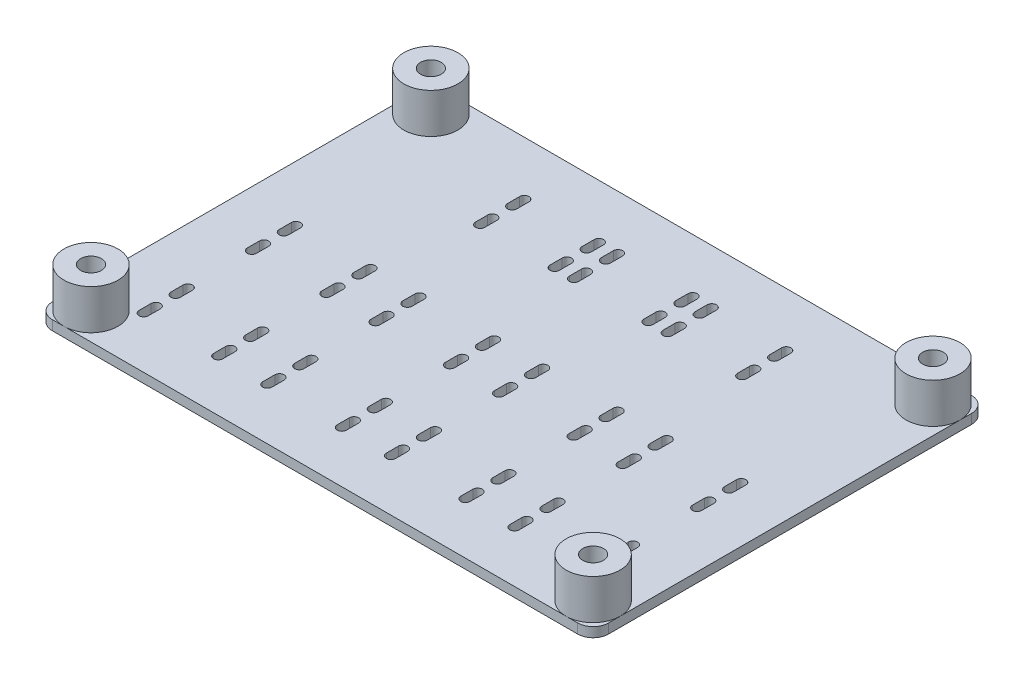
SolidWorks part; units mm, degrees
ref_plane "Front Plane" through (0, 0, 0) normal (0, 0, 1) x (1, 0, 0)
ref_plane "Top Plane" through (0, 0, 0) normal (0, 1, 0) x (1, 0, 0)
ref_plane "Right Plane" through (0, 0, 0) normal (1, 0, 0) x (0, 0, -1)
sketch "Sketch1" plane through (0, 0, 0) normal (0, 1, 0) x (1, 0, 0)
  line L0 (-36.605, 1.085) -> (-36.605, -0.915) construction
  line L1 (-41.275, -27.94) -> (41.275, -27.94) construction
  line L2 (-41.275, -27.94) -> (-41.275, 27.94) construction
  line L3 (-41.275, 27.94) -> (41.275, 27.94) construction
  line L4 (41.275, -27.94) -> (41.275, 27.94) construction
  line L5 (-41.275, -27.94) -> (41.275, 27.94) construction
  line L6 (-41.275, 27.94) -> (41.275, -27.94) construction
  line L7 (-45.72, -32.385) -> (45.72, -32.385)
  line L8 (-45.72, -32.385) -> (-45.72, 32.385)
  line L9 (-45.72, 32.385) -> (45.72, 32.385)
  line L10 (45.72, -32.385) -> (45.72, 32.385)
  line L11 (-45.72, -32.385) -> (45.72, 32.385) construction
  line L12 (-45.72, 32.385) -> (45.72, -32.385) construction
  line L13 (-30.48, -2.54) -> (30.48, -2.54) construction
  line L14 (-16.285, -5.165) -> (-4.035, -5.165) construction
  line L15 (-55, 0) -> (55, 0) construction
  line L16 (0, -55) -> (0, 55) construction
  line L17 (-15.1961, -11.43) -> (15.1961, -11.43) construction
  line L18 (-36.605, -5.165) -> (-24.355, -5.165) construction
  line L19 (-36.605, -5.165) -> (-36.605, 0.085) construction
  line L20 (-36.605, 0.085) -> (-24.355, 0.085) construction
  line L21 (-24.355, -5.165) -> (-24.355, 0.085) construction
  line L22 (-36.605, -5.165) -> (-24.355, 0.085) construction
  line L23 (-36.605, 0.085) -> (-24.355, -5.165) construction
  line L28 (-16.285, -5.165) -> (-16.285, 0.085) construction
  line L34 (-16.285, 0.085) -> (-4.035, 0.085) construction
  line L36 (-4.035, -5.165) -> (-4.035, 0.085) construction
  line L37 (-16.285, -5.165) -> (-4.035, 0.085) construction
  line L38 (-16.285, 0.085) -> (-4.035, -5.165) construction
  line L39 (4.035, -5.165) -> (16.285, -5.165) construction
  line L40 (4.035, -5.165) -> (4.035, 0.085) construction
  line L41 (4.035, 0.085) -> (16.285, 0.085) construction
  line L42 (16.285, -5.165) -> (16.285, 0.085) construction
  line L43 (4.035, -5.165) -> (16.285, 0.085) construction
  line L44 (4.035, 0.085) -> (16.285, -5.165) construction
  line L45 (24.355, -5.165) -> (36.605, -5.165) construction
  line L46 (24.355, -5.165) -> (24.355, 0.085) construction
  line L47 (24.355, 0.085) -> (36.605, 0.085) construction
  line L48 (36.605, -5.165) -> (36.605, 0.085) construction
  line L49 (24.355, -5.165) -> (36.605, 0.085) construction
  line L50 (24.355, 0.085) -> (36.605, -5.165) construction
  line L51 (-35.843, 1.085) -> (-35.843, -0.915)
  line L52 (-37.367, 1.085) -> (-37.367, -0.915)
  line L53 (-24.355, 1.085) -> (-24.355, -0.915) construction
  line L54 (-23.593, 1.085) -> (-23.593, -0.915)
  line L55 (-25.117, 1.085) -> (-25.117, -0.915)
  line L56 (-36.605, -4.165) -> (-36.605, -6.165) construction
  line L57 (-35.843, -4.165) -> (-35.843, -6.165)
  line L58 (-37.367, -4.165) -> (-37.367, -6.165)
  line L59 (-24.355, -4.165) -> (-24.355, -6.165) construction
  line L60 (-23.593, -4.165) -> (-23.593, -6.165)
  line L61 (-25.117, -4.165) -> (-25.117, -6.165)
  line L62 (-16.285, 1.085) -> (-16.285, -0.915) construction
  line L63 (-15.523, 1.085) -> (-15.523, -0.915)
  line L64 (-17.047, 1.085) -> (-17.047, -0.915)
  line L65 (-4.035, 1.085) -> (-4.035, -0.915) construction
  line L66 (-3.273, 1.085) -> (-3.273, -0.915)
  line L67 (-4.797, 1.085) -> (-4.797, -0.915)
  line L68 (-16.285, -4.165) -> (-16.285, -6.165) construction
  line L69 (-15.523, -4.165) -> (-15.523, -6.165)
  line L70 (-17.047, -4.165) -> (-17.047, -6.165)
  line L71 (-4.035, -4.165) -> (-4.035, -6.165) construction
  line L72 (-3.273, -4.165) -> (-3.273, -6.165)
  line L73 (-4.797, -4.165) -> (-4.797, -6.165)
  line L74 (4.035, 1.085) -> (4.035, -0.915) construction
  line L75 (4.797, 1.085) -> (4.797, -0.915)
  line L76 (3.273, 1.085) -> (3.273, -0.915)
  line L77 (16.285, 1.085) -> (16.285, -0.915) construction
  line L78 (17.047, 1.085) -> (17.047, -0.915)
  line L79 (15.523, 1.085) -> (15.523, -0.915)
  line L80 (4.035, -4.165) -> (4.035, -6.165) construction
  line L81 (4.797, -4.165) -> (4.797, -6.165)
  line L82 (3.273, -4.165) -> (3.273, -6.165)
  line L83 (16.285, -4.165) -> (16.285, -6.165) construction
  line L84 (17.047, -4.165) -> (17.047, -6.165)
  line L85 (15.523, -4.165) -> (15.523, -6.165)
  line L86 (24.355, 1.085) -> (24.355, -0.915) construction
  line L87 (25.117, 1.085) -> (25.117, -0.915)
  line L88 (23.593, 1.085) -> (23.593, -0.915)
  line L89 (24.355, -4.165) -> (24.355, -6.165) construction
  line L90 (25.117, -4.165) -> (25.117, -6.165)
  line L91 (23.593, -4.165) -> (23.593, -6.165)
  line L92 (36.605, -4.165) -> (36.605, -6.165) construction
  line L93 (37.367, -4.165) -> (37.367, -6.165)
  line L94 (35.843, -4.165) -> (35.843, -6.165)
  line L95 (24.355, -18.695) -> (24.355, -16.695) construction
  line L98 (36.605, 1.085) -> (36.605, -0.915) construction
  line L99 (37.367, 1.085) -> (37.367, -0.915)
  line L100 (35.843, 1.085) -> (35.843, -0.915)
  line L101 (25.117, -18.695) -> (25.117, -16.695)
  line L102 (23.593, -18.695) -> (23.593, -16.695)
  line L103 (24.355, -23.945) -> (24.355, -21.945) construction
  line L104 (25.117, -23.945) -> (25.117, -21.945)
  line L105 (23.593, -23.945) -> (23.593, -21.945)
  line L106 (16.285, -23.945) -> (16.285, -21.945) construction
  line L107 (17.047, -23.945) -> (17.047, -21.945)
  line L108 (15.523, -23.945) -> (15.523, -21.945)
  line L109 (16.285, -18.695) -> (16.285, -16.695) construction
  line L110 (17.047, -18.695) -> (17.047, -16.695)
  line L111 (15.523, -18.695) -> (15.523, -16.695)
  line L112 (4.035, -23.945) -> (4.035, -21.945) construction
  line L113 (4.797, -23.945) -> (4.797, -21.945)
  line L114 (3.273, -23.945) -> (3.273, -21.945)
  line L115 (4.035, -18.695) -> (4.035, -16.695) construction
  line L116 (4.797, -18.695) -> (4.797, -16.695)
  line L117 (3.273, -18.695) -> (3.273, -16.695)
  line L118 (-4.035, -18.695) -> (-4.035, -16.695) construction
  line L119 (-3.273, -18.695) -> (-3.273, -16.695)
  line L120 (-4.797, -18.695) -> (-4.797, -16.695)
  line L121 (-4.035, -23.945) -> (-4.035, -21.945) construction
  line L122 (-3.273, -23.945) -> (-3.273, -21.945)
  line L123 (-4.797, -23.945) -> (-4.797, -21.945)
  line L124 (-16.285, -23.945) -> (-16.285, -21.945) construction
  line L125 (-15.523, -23.945) -> (-15.523, -21.945)
  line L126 (-17.047, -23.945) -> (-17.047, -21.945)
  line L127 (-16.285, -18.695) -> (-16.285, -16.695) construction
  line L128 (-15.523, -18.695) -> (-15.523, -16.695)
  line L129 (-17.047, -18.695) -> (-17.047, -16.695)
  line L130 (-24.355, -23.945) -> (-24.355, -21.945) construction
  line L131 (-23.593, -23.945) -> (-23.593, -21.945)
  line L132 (-25.117, -23.945) -> (-25.117, -21.945)
  line L133 (-24.355, -18.695) -> (-24.355, -16.695) construction
  line L134 (-23.593, -18.695) -> (-23.593, -16.695)
  line L135 (-25.117, -18.695) -> (-25.117, -16.695)
  line L136 (-36.605, -18.695) -> (-36.605, -16.695) construction
  line L137 (-35.843, -18.695) -> (-35.843, -16.695)
  line L138 (-37.367, -18.695) -> (-37.367, -16.695)
  line L139 (-36.605, -23.945) -> (-36.605, -21.945) construction
  line L140 (-35.843, -23.945) -> (-35.843, -21.945)
  line L141 (-37.367, -23.945) -> (-37.367, -21.945)
  line L142 (36.605, -23.945) -> (36.605, -21.945) construction
  line L143 (37.367, -23.945) -> (37.367, -21.945)
  line L144 (35.843, -23.945) -> (35.843, -21.945)
  line L145 (36.605, -18.695) -> (36.605, -16.695) construction
  line L146 (37.367, -18.695) -> (37.367, -16.695)
  line L147 (35.843, -18.695) -> (35.843, -16.695)
  line L148 (0, -2.54) -> (0, 19.9314) construction
  line L149 (-15.41, 19.9314) -> (15.41, 19.9314) construction
  line L150 (-21.535, 21.5564) -> (-21.535, 23.5564) construction
  line L151 (-6.125, 17.3064) -> (6.125, 17.3064) construction
  line L152 (-6.125, 17.3064) -> (-6.125, 22.5564) construction
  line L153 (-6.125, 22.5564) -> (6.125, 22.5564) construction
  line L154 (6.125, 17.3064) -> (6.125, 22.5564) construction
  line L155 (-6.125, 17.3064) -> (6.125, 22.5564) construction
  line L156 (-6.125, 22.5564) -> (6.125, 17.3064) construction
  line L157 (-21.535, 17.3064) -> (-9.285, 17.3064) construction
  line L158 (-21.535, 17.3064) -> (-21.535, 22.5564) construction
  line L159 (-21.535, 22.5564) -> (-9.285, 22.5564) construction
  line L160 (-9.285, 17.3064) -> (-9.285, 22.5564) construction
  line L161 (-21.535, 17.3064) -> (-9.285, 22.5564) construction
  line L162 (-21.535, 22.5564) -> (-9.285, 17.3064) construction
  line L163 (9.285, 17.3064) -> (21.535, 17.3064) construction
  line L164 (9.285, 17.3064) -> (9.285, 22.5564) construction
  line L165 (9.285, 22.5564) -> (21.535, 22.5564) construction
  line L166 (21.535, 17.3064) -> (21.535, 22.5564) construction
  line L167 (9.285, 17.3064) -> (21.535, 22.5564) construction
  line L168 (9.285, 22.5564) -> (21.535, 17.3064) construction
  line L169 (-22.297, 21.5564) -> (-22.297, 23.5564)
  line L170 (-20.773, 21.5564) -> (-20.773, 23.5564)
  line L171 (9.285, 21.5564) -> (9.285, 23.5564) construction
  line L172 (8.523, 21.5564) -> (8.523, 23.5564)
  line L173 (10.047, 21.5564) -> (10.047, 23.5564)
  line L174 (6.125, 21.5564) -> (6.125, 23.5564) construction
  line L175 (5.363, 21.5564) -> (5.363, 23.5564)
  line L176 (6.887, 21.5564) -> (6.887, 23.5564)
  line L177 (-9.285, 21.5564) -> (-9.285, 23.5564) construction
  line L178 (-10.047, 21.5564) -> (-10.047, 23.5564)
  line L179 (-8.523, 21.5564) -> (-8.523, 23.5564)
  line L180 (-6.125, 21.5564) -> (-6.125, 23.5564) construction
  line L181 (-6.887, 21.5564) -> (-6.887, 23.5564)
  line L182 (-5.363, 21.5564) -> (-5.363, 23.5564)
  line L183 (21.535, 21.5564) -> (21.535, 23.5564) construction
  line L184 (20.773, 21.5564) -> (20.773, 23.5564)
  line L185 (22.297, 21.5564) -> (22.297, 23.5564)
  line L186 (21.535, 18.3064) -> (21.535, 16.3064) construction
  line L187 (20.773, 18.3064) -> (20.773, 16.3064)
  line L188 (22.297, 18.3064) -> (22.297, 16.3064)
  line L189 (9.285, 18.3064) -> (9.285, 16.3064) construction
  line L190 (8.523, 18.3064) -> (8.523, 16.3064)
  line L191 (10.047, 18.3064) -> (10.047, 16.3064)
  line L192 (6.125, 18.3064) -> (6.125, 16.3064) construction
  line L193 (5.363, 18.3064) -> (5.363, 16.3064)
  line L194 (6.887, 18.3064) -> (6.887, 16.3064)
  line L195 (-6.125, 18.3064) -> (-6.125, 16.3064) construction
  line L196 (-6.887, 18.3064) -> (-6.887, 16.3064)
  line L197 (-5.363, 18.3064) -> (-5.363, 16.3064)
  line L198 (-9.285, 18.3064) -> (-9.285, 16.3064) construction
  line L199 (-10.047, 18.3064) -> (-10.047, 16.3064)
  line L200 (-8.523, 18.3064) -> (-8.523, 16.3064)
  line L201 (-21.535, 18.3064) -> (-21.535, 16.3064) construction
  line L202 (-22.297, 18.3064) -> (-22.297, 16.3064)
  line L203 (-20.773, 18.3064) -> (-20.773, 16.3064)
  arc A4 (-35.843, 1.085) -> (-37.367, 1.085) centre (-36.605, 1.085) ccw
  arc A5 (-37.367, -0.915) -> (-35.843, -0.915) centre (-36.605, -0.915) ccw
  arc A6 (-23.593, 1.085) -> (-25.117, 1.085) centre (-24.355, 1.085) ccw
  arc A7 (-25.117, -0.915) -> (-23.593, -0.915) centre (-24.355, -0.915) ccw
  arc A8 (-35.843, -4.165) -> (-37.367, -4.165) centre (-36.605, -4.165) ccw
  arc A9 (-37.367, -6.165) -> (-35.843, -6.165) centre (-36.605, -6.165) ccw
  arc A10 (-23.593, -4.165) -> (-25.117, -4.165) centre (-24.355, -4.165) ccw
  arc A11 (-25.117, -6.165) -> (-23.593, -6.165) centre (-24.355, -6.165) ccw
  arc A12 (-15.523, 1.085) -> (-17.047, 1.085) centre (-16.285, 1.085) ccw
  arc A13 (-17.047, -0.915) -> (-15.523, -0.915) centre (-16.285, -0.915) ccw
  arc A14 (-3.273, 1.085) -> (-4.797, 1.085) centre (-4.035, 1.085) ccw
  arc A15 (-4.797, -0.915) -> (-3.273, -0.915) centre (-4.035, -0.915) ccw
  arc A16 (-15.523, -4.165) -> (-17.047, -4.165) centre (-16.285, -4.165) ccw
  arc A17 (-17.047, -6.165) -> (-15.523, -6.165) centre (-16.285, -6.165) ccw
  arc A18 (-3.273, -4.165) -> (-4.797, -4.165) centre (-4.035, -4.165) ccw
  arc A19 (-4.797, -6.165) -> (-3.273, -6.165) centre (-4.035, -6.165) ccw
  arc A20 (4.797, 1.085) -> (3.273, 1.085) centre (4.035, 1.085) ccw
  arc A21 (3.273, -0.915) -> (4.797, -0.915) centre (4.035, -0.915) ccw
  arc A22 (17.047, 1.085) -> (15.523, 1.085) centre (16.285, 1.085) ccw
  arc A23 (15.523, -0.915) -> (17.047, -0.915) centre (16.285, -0.915) ccw
  arc A24 (4.797, -4.165) -> (3.273, -4.165) centre (4.035, -4.165) ccw
  arc A25 (3.273, -6.165) -> (4.797, -6.165) centre (4.035, -6.165) ccw
  arc A26 (17.047, -4.165) -> (15.523, -4.165) centre (16.285, -4.165) ccw
  arc A27 (15.523, -6.165) -> (17.047, -6.165) centre (16.285, -6.165) ccw
  arc A28 (25.117, 1.085) -> (23.593, 1.085) centre (24.355, 1.085) ccw
  arc A29 (23.593, -0.915) -> (25.117, -0.915) centre (24.355, -0.915) ccw
  arc A30 (25.117, -4.165) -> (23.593, -4.165) centre (24.355, -4.165) ccw
  arc A31 (23.593, -6.165) -> (25.117, -6.165) centre (24.355, -6.165) ccw
  arc A32 (37.367, -4.165) -> (35.843, -4.165) centre (36.605, -4.165) ccw
  arc A33 (35.843, -6.165) -> (37.367, -6.165) centre (36.605, -6.165) ccw
  arc A36 (37.367, 1.085) -> (35.843, 1.085) centre (36.605, 1.085) ccw
  arc A37 (35.843, -0.915) -> (37.367, -0.915) centre (36.605, -0.915) ccw
  arc A38 (25.117, -18.695) -> (23.593, -18.695) centre (24.355, -18.695) cw
  arc A39 (23.593, -16.695) -> (25.117, -16.695) centre (24.355, -16.695) cw
  arc A40 (25.117, -23.945) -> (23.593, -23.945) centre (24.355, -23.945) cw
  arc A41 (23.593, -21.945) -> (25.117, -21.945) centre (24.355, -21.945) cw
  arc A42 (17.047, -23.945) -> (15.523, -23.945) centre (16.285, -23.945) cw
  arc A43 (15.523, -21.945) -> (17.047, -21.945) centre (16.285, -21.945) cw
  arc A44 (17.047, -18.695) -> (15.523, -18.695) centre (16.285, -18.695) cw
  arc A45 (15.523, -16.695) -> (17.047, -16.695) centre (16.285, -16.695) cw
  arc A46 (4.797, -23.945) -> (3.273, -23.945) centre (4.035, -23.945) cw
  arc A47 (3.273, -21.945) -> (4.797, -21.945) centre (4.035, -21.945) cw
  arc A48 (4.797, -18.695) -> (3.273, -18.695) centre (4.035, -18.695) cw
  arc A49 (3.273, -16.695) -> (4.797, -16.695) centre (4.035, -16.695) cw
  arc A50 (-3.273, -18.695) -> (-4.797, -18.695) centre (-4.035, -18.695) cw
  arc A51 (-4.797, -16.695) -> (-3.273, -16.695) centre (-4.035, -16.695) cw
  arc A52 (-3.273, -23.945) -> (-4.797, -23.945) centre (-4.035, -23.945) cw
  arc A53 (-4.797, -21.945) -> (-3.273, -21.945) centre (-4.035, -21.945) cw
  arc A54 (-15.523, -23.945) -> (-17.047, -23.945) centre (-16.285, -23.945) cw
  arc A55 (-17.047, -21.945) -> (-15.523, -21.945) centre (-16.285, -21.945) cw
  arc A56 (-15.523, -18.695) -> (-17.047, -18.695) centre (-16.285, -18.695) cw
  arc A57 (-17.047, -16.695) -> (-15.523, -16.695) centre (-16.285, -16.695) cw
  arc A58 (-23.593, -23.945) -> (-25.117, -23.945) centre (-24.355, -23.945) cw
  arc A59 (-25.117, -21.945) -> (-23.593, -21.945) centre (-24.355, -21.945) cw
  arc A60 (-23.593, -18.695) -> (-25.117, -18.695) centre (-24.355, -18.695) cw
  arc A61 (-25.117, -16.695) -> (-23.593, -16.695) centre (-24.355, -16.695) cw
  arc A62 (-35.843, -18.695) -> (-37.367, -18.695) centre (-36.605, -18.695) cw
  arc A63 (-37.367, -16.695) -> (-35.843, -16.695) centre (-36.605, -16.695) cw
  arc A64 (-35.843, -23.945) -> (-37.367, -23.945) centre (-36.605, -23.945) cw
  arc A65 (-37.367, -21.945) -> (-35.843, -21.945) centre (-36.605, -21.945) cw
  arc A66 (37.367, -23.945) -> (35.843, -23.945) centre (36.605, -23.945) cw
  arc A67 (35.843, -21.945) -> (37.367, -21.945) centre (36.605, -21.945) cw
  arc A68 (37.367, -18.695) -> (35.843, -18.695) centre (36.605, -18.695) cw
  arc A69 (35.843, -16.695) -> (37.367, -16.695) centre (36.605, -16.695) cw
  arc A70 (-22.297, 21.5564) -> (-20.773, 21.5564) centre (-21.535, 21.5564) ccw
  arc A71 (-20.773, 23.5564) -> (-22.297, 23.5564) centre (-21.535, 23.5564) ccw
  arc A72 (8.523, 21.5564) -> (10.047, 21.5564) centre (9.285, 21.5564) ccw
  arc A73 (10.047, 23.5564) -> (8.523, 23.5564) centre (9.285, 23.5564) ccw
  arc A74 (5.363, 21.5564) -> (6.887, 21.5564) centre (6.125, 21.5564) ccw
  arc A75 (6.887, 23.5564) -> (5.363, 23.5564) centre (6.125, 23.5564) ccw
  arc A76 (-10.047, 21.5564) -> (-8.523, 21.5564) centre (-9.285, 21.5564) ccw
  arc A77 (-8.523, 23.5564) -> (-10.047, 23.5564) centre (-9.285, 23.5564) ccw
  arc A78 (-6.887, 21.5564) -> (-5.363, 21.5564) centre (-6.125, 21.5564) ccw
  arc A79 (-5.363, 23.5564) -> (-6.887, 23.5564) centre (-6.125, 23.5564) ccw
  arc A80 (20.773, 21.5564) -> (22.297, 21.5564) centre (21.535, 21.5564) ccw
  arc A81 (22.297, 23.5564) -> (20.773, 23.5564) centre (21.535, 23.5564) ccw
  arc A82 (20.773, 18.3064) -> (22.297, 18.3064) centre (21.535, 18.3064) cw
  arc A83 (22.297, 16.3064) -> (20.773, 16.3064) centre (21.535, 16.3064) cw
  arc A84 (8.523, 18.3064) -> (10.047, 18.3064) centre (9.285, 18.3064) cw
  arc A85 (10.047, 16.3064) -> (8.523, 16.3064) centre (9.285, 16.3064) cw
  arc A86 (5.363, 18.3064) -> (6.887, 18.3064) centre (6.125, 18.3064) cw
  arc A87 (6.887, 16.3064) -> (5.363, 16.3064) centre (6.125, 16.3064) cw
  arc A88 (-6.887, 18.3064) -> (-5.363, 18.3064) centre (-6.125, 18.3064) cw
  arc A89 (-5.363, 16.3064) -> (-6.887, 16.3064) centre (-6.125, 16.3064) cw
  arc A90 (-10.047, 18.3064) -> (-8.523, 18.3064) centre (-9.285, 18.3064) cw
  arc A91 (-8.523, 16.3064) -> (-10.047, 16.3064) centre (-9.285, 16.3064) cw
  arc A92 (-22.297, 18.3064) -> (-20.773, 18.3064) centre (-21.535, 18.3064) cw
  arc A93 (-20.773, 16.3064) -> (-22.297, 16.3064) centre (-21.535, 16.3064) cw
  circle A94 centre (-41.275, 27.94) radius 4.445 construction
  point P0 (0, 0)
  point P6 (0, 0)
  point P18 (0, -2.54)
  point P20 (-10.16, -2.54)
  point P21 (-10.16, -2.54)
  point P31 (10.16, -2.54)
  point P33 (10.16, -2.54)
  point P43 (0, -11.43)
  point P47 (-36.605, 0.085)
  point P55 (-24.355, 0.085)
  point P60 (0, 19.9314)
  point P63 (-36.605, -5.165)
  point P71 (-24.355, -5.165)
  point P79 (-16.285, 0.085)
  point P87 (-4.035, 0.085)
  point P95 (-16.285, -5.165)
  point P103 (-4.035, -5.165)
  point P112 (4.035, 0.085)
  point P119 (16.285, 0.085)
  point P126 (4.035, -5.165)
  point P133 (16.285, -5.165)
  point P144 (-21.535, 22.5564)
  point P153 (24.355, 0.085)
  point P158 (9.285, 22.5564)
  point P162 (24.355, -5.165)
  point P170 (36.605, -5.165)
  point P180 (24.355, -17.695)
  point P185 (36.605, 0.085)
  point P195 (24.355, -22.945)
  point P202 (16.285, -22.945)
  point P209 (16.285, -17.695)
  point P216 (4.035, -22.945)
  point P223 (4.035, -17.695)
  point P230 (-4.035, -17.695)
  point P237 (-4.035, -22.945)
  point P244 (-16.285, -22.945)
  point P251 (-16.285, -17.695)
  point P258 (-24.355, -22.945)
  point P265 (-24.355, -17.695)
  point P272 (-36.605, -17.695)
  point P279 (-36.605, -22.945)
  point P286 (36.605, -22.945)
  point P293 (36.605, -17.695)
  point P299 (6.125, 22.5564)
  point P308 (-9.285, 22.5564)
  point P316 (-6.125, 22.5564)
  point P333 (21.535, 22.5564)
  point P341 (21.535, 17.3064)
  point P348 (9.285, 17.3064)
  point P355 (6.125, 17.3064)
  point P362 (-6.125, 17.3064)
  point P369 (-9.285, 17.3064)
  point P376 (-21.535, 17.3064)
  dimension "D5" = 22.4714
  dimension "D14" = 0.762
  dimension "D1" = 82.55
  dimension "D2" = 55.88
  dimension "D3" = 91.44
  dimension "D6" = 60.96
  dimension "D7" = 2.54
  dimension "D8" = 12.25
  dimension "D9" = 20.32
  dimension "D10" = 20.32
  dimension "D11" = 8.89
  dimension "D12" = 5.25
  dimension "D13" = 2
  dimension "D15" = 30.82
extrude "Boss-Extrude1" add sketch "Sketch1" along normal blind 1.5875
sketch "Sketch2" plane through (0, 1.5875, 0) normal (0, 1, 0) x (1, 0, 0)
  line L0 (-45.72, 32.385) -> (-45.72, -32.385) construction
  line L1 (-41.275, -27.94) -> (41.275, -27.94) construction
  line L2 (-41.275, -27.94) -> (-41.275, 27.94) construction
  line L3 (-41.275, 27.94) -> (41.275, 27.94) construction
  line L4 (41.275, -27.94) -> (41.275, 27.94) construction
  line L5 (-41.275, -27.94) -> (41.275, 27.94) construction
  line L6 (-41.275, 27.94) -> (41.275, -27.94) construction
  line L7 (0, -55) -> (0, 55) construction
  line L8 (-55, 0) -> (55, 0) construction
  circle A1 centre (-41.275, 27.94) radius 4.445
  circle A2 centre (41.275, 27.94) radius 4.445
  circle A4 centre (41.275, -27.94) radius 4.445
  circle A6 centre (-41.275, -27.94) radius 4.445
  point P0 (0, 0)
  dimension "D1" = 82.55
  dimension "D2" = 55.88
extrude "Boss-Extrude2" add sketch "Sketch2" along normal blind 6.5786
sketch "Sketch3" plane through (0, 8.1661, 0) normal (0, 1, 0) x (1, 0, 0)
  circle A0 centre (-41.275, 27.94) radius 1.7
  circle A1 centre (41.275, 27.94) radius 1.7
  circle A2 centre (41.275, -27.94) radius 1.7
  circle A3 centre (-41.275, -27.94) radius 1.7
  dimension "D1" = 3.4
extrude "Cut-Extrude1" cut sketch "Sketch3" against normal through all
fillet "Fillet2" radius 2.54 4 edges at (45.72, 0.7937, 32.385) (-45.72, 0.7937, 32.385) (-45.72, 0.7937, -32.385) (45.72, 0.7937, -32.385)
